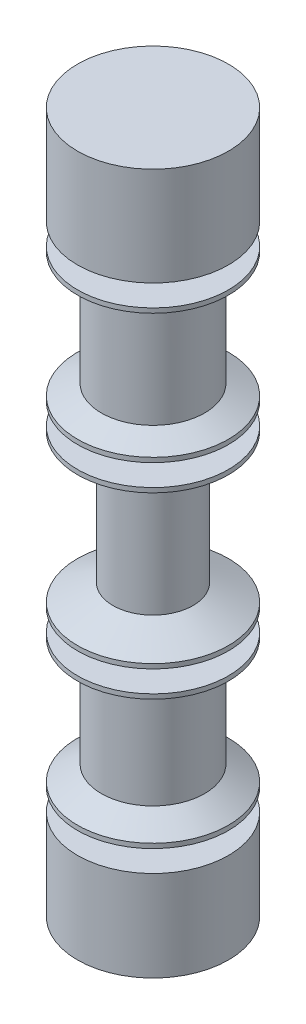
SolidWorks part; units mm, degrees
material "6061-T6 (SS)"
ref_plane "Front Plane" through (0, 0, 0) normal (0, 0, 1) x (1, 0, 0)
ref_plane "Top Plane" through (0, 0, 0) normal (0, 1, 0) x (1, 0, 0)
ref_plane "Right Plane" through (0, 0, 0) normal (1, 0, 0) x (0, 0, -1)
sketch "MidBodyS" plane through (0, 0, 0) normal (0, 1, 0) x (1, 0, 0)
  circle A0 centre (0, 0) radius 2.6
  dimension "Dia" = 5.2
extrude "MidBody" add sketch "MidBodyS" along normal blind 3.7
sketch "MidORingBaseS" plane through (0, 0, 0) normal (0, 0, 1) x (1, 0, 0)
  line L0 (2.6, 3.7) -> (4.9, 4.8)
  line L1 (4.9, 4.8) -> (4.9, 5.1)
  line L2 (4.9, 5.1) -> (0, 5.1)
  line L3 (0, 5.1) -> (0, 3.7) construction
  line L4 (2.6, 3.7) -> (-2.6, 3.7) construction
  line L5 (0, 3.7) -> (2.6, 3.7)
  line L6 (0, 5.1) -> (0, 3.7) construction
  line L7 (0, 5.1) -> (0, 3.7)
  dimension "EdgeHeight" = 0.3
  dimension "Height" = 1.4
  dimension "DiaControl" = 2.3
  dimension "RefDia" = 9.8
revolve "MidORingBase" add sketch "MidORingBaseS" angle 360 about L7
sketch "MidORingBodyS" plane through (0, 5.1, 0) normal (0, 1, 0) x (1, 0, 0)
  circle A0 centre (0, 0) radius 2.5
  circle A2 centre (0, 0) radius 4.9 construction
  dimension "RefDia" = 5
  dimension "DiaContro" = 2.4
extrude "MidORingBody" add sketch "MidORingBodyS" along normal blind 1.4
sketch "MidORingTopBaseS" plane through (0, 0, 0) normal (0, 0, 1) x (1, 0, 0)
  line L0 (0, 6.5) -> (4.9, 6.5)
  line L1 (2.5, 6.5) -> (-2.5, 6.5) construction
  line L2 (4.9, 6.5) -> (4.9, 6.8)
  line L3 (4.9, 6.8) -> (3.35, 7.5)
  line L4 (3.35, 7.5) -> (0, 7.5)
  line L5 (0, 6.5) -> (0, 7.5) construction
  line L6 (4.9, 4.8) -> (4.9, 5.1) construction
  line L7 (0, 6.5) -> (0, 7.5)
  point P9 (2.9944, 8.2)
  dimension "Height" = 1
  dimension "DiaControl" = 1.55
  dimension "RefDia" = 6.7
revolve "MidORingTopBase" add sketch "MidORingTopBaseS" angle 360 about L5
sketch "ExtendedMidBodyS" plane through (0, 7.5, 0) normal (0, 1, 0) x (1, 0, 0)
  circle A1 centre (0, 0) radius 3.35
  circle A2 centre (0, 0) radius 3.35
  dimension "D1" = 0
extrude "ExtendedMidBody" add sketch "ExtendedMidBodyS" along normal blind 6.4
sketch "EndORingBaseS" plane through (0, 0, 0) normal (0, 0, 1) x (1, 0, 0)
  line L0 (0, 13.9) -> (0, 15.2) construction
  line L1 (3.35, 13.9) -> (-3.35, 13.9) construction
  line L2 (0, 15.2) -> (4.9, 15.2)
  line L3 (4.9, 15.2) -> (4.9, 14.9)
  line L4 (4.9, 14.9) -> (3.35, 13.9)
  line L5 (3.35, 13.9) -> (0, 13.9)
  line L6 (4.9, 4.8) -> (4.9, 5.1) construction
  line L7 (3.35, 7.5) -> (3.35, 13.9) construction
  line L8 (0, 13.9) -> (0, 15.2)
  point P10 (3.35, 14.7)
  dimension "Height" = 1.3
revolve "EndORingBase" add sketch "EndORingBaseS" angle 360 about L0
sketch "EndORingBodyS" plane through (0, 15.2, 0) normal (0, 1, 0) x (1, 0, 0)
  circle A0 centre (0, 0) radius 2.5
  circle A1 centre (0, 0) radius 4.9 construction
  dimension "DiaControl" = 2.4
extrude "EndORingBody" add sketch "EndORingBodyS" along normal blind 1.4
sketch "EndBodyS" plane through (0, 16.6, 0) normal (0, 1, 0) x (1, 0, 0)
  circle A0 centre (0, 0) radius 4.9
  circle A1 centre (0, 0) radius 4.9 construction
extrude "EndBody" add sketch "EndBodyS" along normal blind 6.4
mirror "HalfBodyVM" about plane through (0, 0, 0) normal (0, 1, 0) of "EndBody", "MidBody", "MidORingBase", "MidORingBody", "MidORingTopBase", "ExtendedMidBody", "EndORingBase", "EndORingBody"
hole_wizard "Ø4.2 (4.2) Diameter Hole1" positions "Sketch9" profile "HoleProfile" hole size "Ø4.2" standard "ANSI Metric"
sketch "Sketch9" plane through (0, -23, 0) normal (0, -1, 0) x (-1, 0, 0)
  point P0 (0, 0)
sketch "HoleProfile" plane through (0, -23, 0) normal (1, 0, 0) x (0, 0, -1)
  line L0 (0, 0) -> (0, 10.6618)
  line L1 (0, 10.6618) -> (2.1, 9.4)
  line L2 (2.1, 9.4) -> (2.1, 0.4)
  line L3 (2.1, 0.4) -> (2.5, 0)
  line L5 (2.5, 0) -> (0, 0)
  line L6 (-2.1, 0.4) -> (-2.5, 0) construction
  line L10 (0, 10.6618) -> (-2.1, 9.4) construction
  line L11 (0, -6.35) -> (0, 107.95) construction
  dimension "Hole Dia." = 4.2
  dimension "Hole Depth" = 9.4
  dimension "Near C'Sink Dia." = 5
  dimension "Near C'Sink Angle" = 90
  dimension "Drill Angle" = 118
sketch "ChamferS" plane through (0, -23, 0) normal (0, -1, 0) x (1, 0, 0)
  circle A0 centre (0, 0) radius 4
  circle A1 centre (0, 0) radius 4.9 construction
  dimension "RefDia" = 8
  dimension "DiaControl" = 0.9
extrude "Chamfer" cut sketch "ChamferS" against normal through all draft 60 flip side to cut
equation "\"DiaControl@EndORingBodyS\" = \"DiaContro@MidORingBodyS\""
equation "\"Height@EndORingBody\" = \"Height@MidORingBody\""
